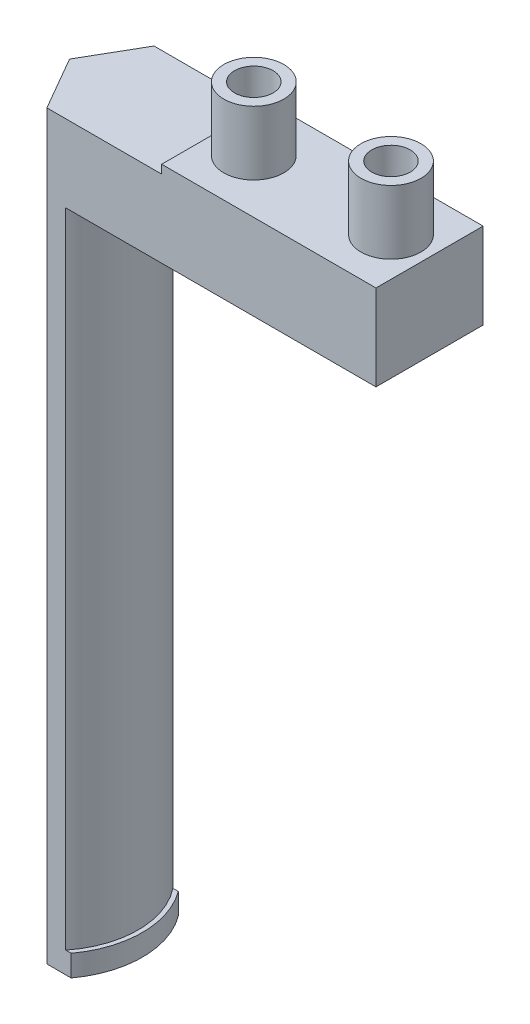
SolidWorks part; units mm, degrees
material "AA380.0-F die"
ref_plane "Piano frontale" through (0, 0, 0) normal (0, 0, 1) x (1, 0, 0)
ref_plane "Piano superiore" through (0, 0, 0) normal (0, 1, 0) x (1, 0, 0)
ref_plane "Piano destro" through (0, 0, 0) normal (1, 0, 0) x (0, 0, -1)
sketch "Schizzo2" plane through (0, 0, 0) normal (0, 0, 1) x (1, 0, 0)
  line L0 (0, 0) -> (-88, 0)
  line L1 (-88, 0) -> (-88, -200)
  line L2 (-88, -200) -> (-48, -200)
  line L3 (-48, -200) -> (-48, -170)
  line L4 (-48, -170) -> (-68, -170)
  line L5 (-68, -170) -> (-68, -20)
  line L6 (-68, -20) -> (0, -20)
  line L7 (0, -20) -> (0, 0)
  dimension "D1" = 88
  dimension "D2" = 20
  dimension "D3" = 200
  dimension "D4" = 20
  dimension "D5" = 30
  dimension "D6" = 20
extrude "Estrusione-Estrusione1" add sketch "Schizzo2" along normal blind 25
sketch "Schizzo3" plane through (0, 0, 0) normal (0, 1, 0) x (1, 0, 0)
  line L0 (0, -12.5) -> (-9, -12.5) construction
  line L1 (0, -25) -> (0, 0) construction
  line L2 (-9, -12.5) -> (-41, -12.5) construction
  circle A0 centre (-41, -12.5) radius 7
  circle A1 centre (-9, -12.5) radius 7
  dimension "D3" = 14
  dimension "D4" = 14
  dimension "D1" = 9
  dimension "D2" = 32
extrude "Estrusione-Estrusione2" add sketch "Schizzo3" along normal blind 14.91
hole_wizard "Foro lamato per Vite M8 a testa cilindrica-1" positions "Schizzo4" profile "Schizzo5" counterbore size "M8" standard "ISO"
sketch "Schizzo4" plane through (0, -20, 0) normal (0, -1, 0) x (-1, 0, 0)
  line L0 (0, -12.5) -> (9, -12.5) construction
  line L1 (0, -25) -> (0, 0) construction
  line L2 (9, -12.5) -> (41, -12.5) construction
  point P0 (9, -12.5)
  point P2 (41, -12.5)
  dimension "D1" = 9
  dimension "D2" = 32
sketch "Schizzo5" plane through (-9, -20, 12.5) normal (1, 0, 0) x (0, 0, -1)
  line L0 (0, 0) -> (0, 34.91)
  line L1 (0, 34.91) -> (4.5, 34.91)
  line L3 (4.5, 34.91) -> (4.5, 8.6)
  line L4 (4.5, 8.6) -> (7.5, 8.6)
  line L5 (7.5, 8.6) -> (7.5, 0)
  line L7 (7.5, 0) -> (0, 0)
  line L11 (0, -6.35) -> (0, 107.95) construction
  dimension "Thru Hole Dia." = 9
  dimension "Thru Hole Depth" = 34.91
  dimension "C'Bore Dia." = 15
  dimension "C'Bore Depth" = 8.6
sketch "Schizzo10" plane through (0, -170, 0) normal (0, 1, 0) x (1, 0, 0)
  line L1 (-68, -25) -> (-68, 0) construction
  line L2 (-72.3875, 0) -> (-68, 0)
  line L4 (-68, 0) -> (-68, -25)
  line L5 (-68, -25) -> (-72.3875, -25)
  arc A0 (-72.3875, -25) -> (-72.3875, 0) centre (-88, -12.5) ccw
  point P5 (-68, -12.5)
  line M3 (-68, 0) -> (-68, -25)
  dimension "D1" = 40
extrude "Taglio-Estrusione3" cut sketch "Schizzo10" along normal up to surface (150 mm away) contours A0 L2 M3 | A0 L5 L4 up to face at (-9, -20, 5)
sketch "Schizzo11" plane through (0, -170, 0) normal (0, 1, 0) x (1, 0, 0)
  line L3 (-48, 0) -> (-72.3875, 0)
  line L4 (-72.3875, -25) -> (-48, -25)
  line L5 (-48, -25) -> (-48, 0)
  line L6 (-48, 0) -> (-72.3875, 0)
  line L7 (-72.3875, -25) -> (-48, -25)
  line L8 (-48, -25) -> (-48, 0)
  line L9 (-49, -24) -> (-49, -1) construction
  line L10 (-70.4287, -24) -> (-49, -24) construction
  line L11 (-49, -1) -> (-70.4287, -1) construction
  arc A0 (-70.4287, -24) -> (-70.4287, -1) centre (-88, -12.5) ccw
  arc A1 (-72.3875, -25) -> (-72.3875, 0) centre (-88, -12.5) ccw
  arc A2 (-72.3875, -25) -> (-72.3875, 0) centre (-88, -12.5) ccw
  arc A3 (-71.1255, -25) -> (-71.1255, 0) centre (-88, -12.5) ccw
  line M10 (-48, 0) -> (-72.3875, 0)
  line M13 (-48, -25) -> (-48, 0)
  dimension "D1" = 0
  dimension "D2" = 1
extrude "Taglio-Estrusione4" cut sketch "Schizzo11" against normal up to surface (30 mm away) contours A3 L7 A0 M13 M10 up to face at (-68, -200, 12.5)
sketch "Schizzo12" plane through (0, -200, 0) normal (0, -1, 0) x (1, 0, 0)
  line L3 (-71.1255, 25) -> (-88, 25)
  line L4 (-88, 25) -> (-88, 0)
  line L5 (-88, 0) -> (-71.1255, 0)
  line L6 (-71.1255, 25) -> (-88, 25)
  line L7 (-88, 25) -> (-88, 0)
  line L8 (-88, 0) -> (-71.1255, 0)
  arc A1 (-71.1255, 0) -> (-71.1255, 25) centre (-88, 12.5) ccw
  arc A2 (-71.1255, 0) -> (-71.1255, 25) centre (-88, 12.5) ccw
  dimension "D1" = 0
extrude "Taglio-Estrusione5" cut sketch "Schizzo12" against normal blind 20
sketch "Schizzo13" plane through (0, -180, 0) normal (0, -1, 0) x (1, 0, 0)
  line L0 (-88, 12.5) -> (-84, 12.5) construction
  line L1 (-88, 25) -> (-88, 0) construction
  line L2 (-84, 12.5) -> (-76.7831, 25)
  line L3 (-84, 12.5) -> (-76.7831, 0)
  line L6 (-71.1255, 25) -> (-88, 25)
  line L7 (-88, 25) -> (-88, 0)
  line L8 (-88, 0) -> (-71.1255, 0)
  line L9 (-71.1255, 25) -> (-88, 25)
  line L10 (-88, 25) -> (-88, 0)
  line L11 (-88, 0) -> (-71.1255, 0)
  arc A1 (-71.1255, 0) -> (-71.1255, 25) centre (-88, 12.5) ccw
  arc A2 (-71.1255, 0) -> (-71.1255, 25) centre (-88, 12.5) ccw
  line M8 (-71.1255, 25) -> (-88, 25)
  line M9 (-88, 25) -> (-88, 0)
  line M10 (-88, 0) -> (-71.1255, 0)
  dimension "D1" = 4
  dimension "D2" = 120
  dimension "D3" = 0
extrude "Taglio-Estrusione6" cut sketch "Schizzo13" against normal up to surface (180 mm away) contours L0 L2 M9 M8 | L0 L10 L3 M10 up to face at (-2, 0, 12.5)
sketch "Schizzo14" plane through (0, -180, 0) normal (0, -1, 0) x (1, 0, 0)
  line L4 (-76.7831, 25) -> (-84, 12.5)
  line L5 (-84, 12.5) -> (-76.7831, 0)
  line L6 (-76.7831, 0) -> (-71.1255, 0)
  line L7 (-71.1255, 25) -> (-76.7831, 25)
  line L8 (-76.7831, 25) -> (-84, 12.5)
  line L9 (-84, 12.5) -> (-76.7831, 0)
  line L10 (-76.7831, 0) -> (-71.1255, 0)
  line L11 (-71.1255, 25) -> (-76.7831, 25)
  arc A1 (-71.1255, 0) -> (-71.1255, 25) centre (-88, 12.5) ccw
  arc A2 (-71.1255, 0) -> (-71.1255, 25) centre (-88, 12.5) ccw
  dimension "D1" = 0
extrude "Taglio-Estrusione7" cut sketch "Schizzo14" against normal blind 5
sketch "Schizzo15" plane through (0, 0, 0) normal (0, 1, 0) x (1, 0, 0)
  line L0 (-50, -41.6325) -> (-50, 17.804)
  line L5 (-76.7831, 0) -> (-84, -12.5)
  line L6 (-84, -12.5) -> (-76.7831, -25)
  line L7 (-76.7831, -25) -> (0, -25)
  line L8 (0, -25) -> (0, 0)
  line L9 (0, 0) -> (-76.7831, 0)
  line L10 (-76.7831, 0) -> (-84, -12.5)
  line L11 (-84, -12.5) -> (-76.7831, -25)
  line L12 (-76.7831, -25) -> (0, -25)
  line L13 (0, -25) -> (0, 0)
  line L14 (0, 0) -> (-76.7831, 0)
  line M9 (-76.7831, 0) -> (-84, -12.5)
  line M10 (-84, -12.5) -> (-76.7831, -25)
  line M11 (-76.7831, -25) -> (0, -25)
  line M13 (0, 0) -> (-76.7831, 0)
  dimension "D2" = 34
  dimension "D1" = 0
extrude "Taglio-Estrusione8" cut sketch "Schizzo15" against normal blind 2 contours L0 M11 M13 M9 M10
